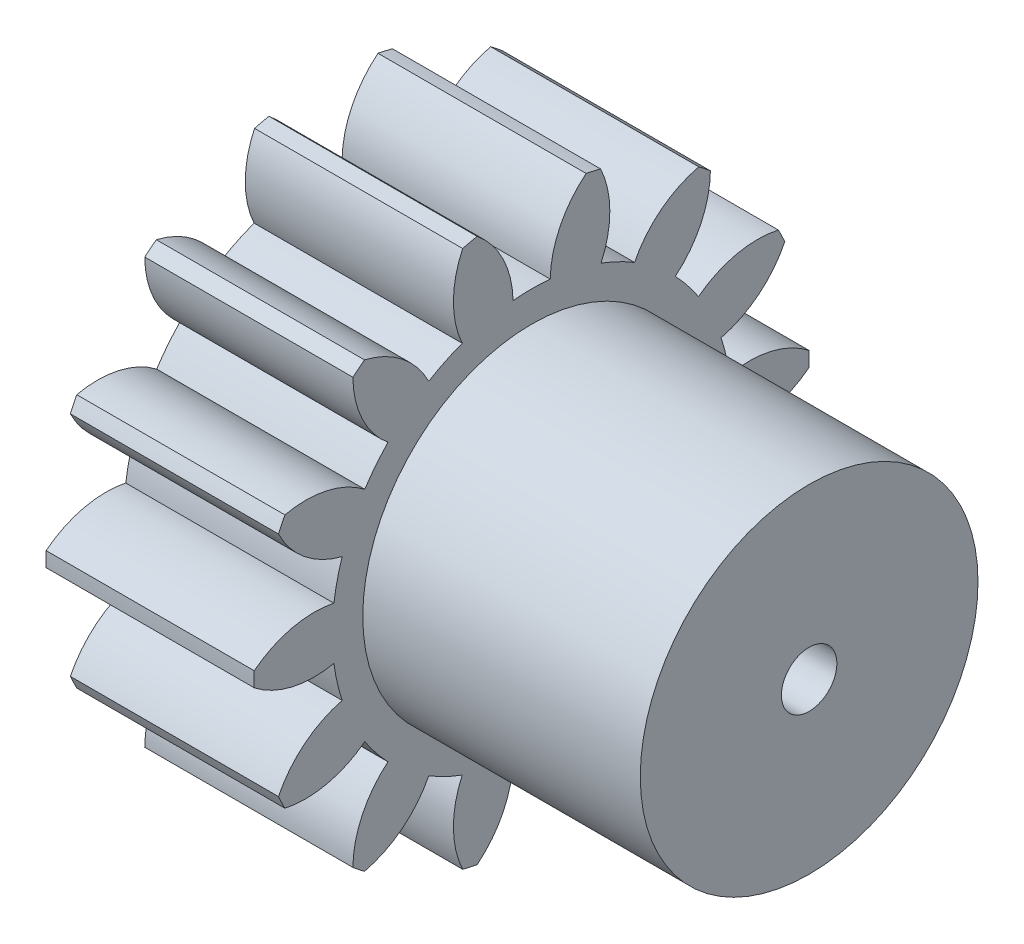
SolidWorks part; units mm, degrees
ref_plane "Plane1" through (0, 0, 0) normal (0, 0, 1) x (1, 0, 0)
ref_plane "Plane2" through (0, 0, 0) normal (0, 1, 0) x (1, 0, 0)
ref_plane "Plane3" through (0, 0, 0) normal (1, 0, 0) x (0, 0, -1)
sketch "HoldingSke" plane through (0, 0, 0) normal (0, 1, 0) x (1, 0, 0)
  line L0 (0, 0) -> (0.3881, -0.0968)
  line L1 (-15, 0) -> (100, 0) construction
  line L2 (0, 0) -> (-2.1039, 2.3779)
  line L3 (0, 0) -> (-11.863, 4.5341)
  line L4 (0, 0) -> (8.3795, 2.0892)
  line L5 (0, 0) -> (-46.8476, -17.4728)
  line L6 (0, 0) -> (-12.4344, -8.3896)
  line L7 (-2.1039, 2.3779) -> (8.6586, 51.2059)
  line L8 (-76.2, 54.61) -> (-75.5, 54.61)
  line L9 (-71.009, 38.7566) -> (-53.1078, 45.2721)
  line L10 (-76.2, 71.12) -> (104.1128, 71.12)
  line L11 (0, 0) -> (-15, 0)
  line L12 (-76.2, 101.6) -> (-76.113, 101.6)
  line L13 (24.9733, 27.94) -> (52.9518, 28.4284)
  line L14 (24.9733, 27.94) -> (24.9743, 27.94)
  line L15 (24.9733, 27.94) -> (100.4006, 29.5858)
  line L16 (-63.627, -2.5) -> (-12.827, -2.5)
  circle A0 centre (0, 0) radius 2
  circle A1 centre (0, 0) radius 14.374
  circle A2 centre (0, 0) radius 37.5
  circle A3 centre (0, 0) radius 2
  dimension "MHD" = 28.748
  dimension "Hub_dia" = 75
  dimension "Bore" = 4
  dimension "MBD" = 4
  dimension "Num_teeth" = 14
  dimension "Pitch" = 0.4
  dimension "Overall_len" = 50
  dimension "Show_teeth" = 14
  dimension "Thickness" = 15
  dimension "OAL" = 50.0001
  dimension "T_dim" = 0.7
  dimension "Ap" = 20
  dimension "H" = 19.05
  dimension "Pitch_radius" = 180.3128
  dimension "Width" = 15
  dimension "Backlash" = 0.087
  dimension "Addendum_fac" = 1
  dimension "Dedendum_fac" = 1.25
  dimension "Clearance_fac" = 0.25
  dimension "Dedendum_add" = 0.001
  dimension "Module" = 2.5
sketch "BasProSke" plane through (0, 0, 0) normal (0, 1, 0) x (1, 0, 0)
  line L0 (-10, 0) -> (60, 0) construction
  line L1 (0, 0) -> (0, 20)
  line L2 (0, 0) -> (15, 0)
  line L3 (15, 0) -> (15, 20)
  line L4 (15, 20) -> (0, 20)
  dimension "Thickness" = 15
  dimension "Diameter" = 40
revolve "Base-Revolve" add sketch "BasProSke" angle 360 about L0
sketch "TooCutSke" plane through (0, 0, 0) normal (1, 0, 0) x (0, 0, -1)
  line L1 (0, 0) -> (0, 107) construction
  line L2 (0, 0) -> (-2.1115, 17.3722) construction
  line L3 (0, 0) -> (-7.7466, 33.9401) construction
  line L4 (-2.1115, 17.3722) -> (-3.8733, 16.97) construction
  arc A0 (1.3395, 14.3115) -> (-1.3395, 14.3115) centre (0, 0) ccw
  arc A1 (3.9542, 19.6311) -> (-3.9542, 19.6311) centre (0, 0) ccw
  circle A2 centre (0, 0) radius 17.5 construction
  circle A3 centre (0, 0) radius 16.4446 construction
  arc A4 (-1.3395, 14.3115) -> (-3.9542, 19.6311) centre (-8.3382, 14.1739) ccw
  arc A5 (3.9542, 19.6311) -> (1.3395, 14.3115) centre (8.3382, 14.1739) ccw
  dimension "Root_dia" = 28.748
  dimension "Overcut_dia" = 40.0508
  dimension "Pitch_dia" = 35
  dimension "Base_dia" = 32.8892
  dimension "Flank_rad" = 7
  dimension "Half_ang" = 12.857
  dimension "Half_CT" = 1.8071
extrude "ToothCut" cut sketch "TooCutSke" along normal through all
fillet "Breaks" [suppressed] radius 0.05
fillet "RootFillets" [suppressed] radius 0.626
pattern_circular "TeethCuts" count 14 every 25.714 about axis through (-10, 0, 0) along (1, 0, 0) of "ToothCut", "RootFillets", "Breaks"
sketch "HubNeaOneSke" plane through (0, 0, 0) normal (-1, 0, 0) x (0, 0, 1)
  circle A0 centre (0, 0) radius 14.374
  dimension "Diameter" = 28.748
extrude "HubNearOne" [suppressed] add sketch "HubNeaOneSke" along normal blind 35.0001
sketch "HubNeaBotSke" plane through (0, 0, 0) normal (-1, 0, 0) x (0, 0, 1)
  circle A0 centre (0, 0) radius 14.374
  dimension "Diameter" = 28.748
extrude "HubNearBoth" [suppressed] add sketch "HubNeaBotSke" along normal blind 17.5
ref_plane "FarPln" through (15, 0, 0) normal (1, 0, 0) x (0, 0, -1)
sketch "HubFarSke" plane through (15, 0, 0) normal (1, 0, 0) x (0, 0, -1)
  circle A0 centre (0, 0) radius 14.374
  dimension "Diameter" = 28.748
extrude "HubFar" [suppressed] add sketch "HubFarSke" along normal blind 17.5
sketch "BorSke" plane through (0, 0, 0) normal (1, 0, 0) x (0, 0, -1)
  circle A0 centre (0, 0) radius 2
  dimension "Diameter" = 4
extrude "Bore" cut sketch "BorSke" along normal mid plane 100.0001
sketch "KeySke" plane through (0, 0, 0) normal (1, 0, 0) x (0, 0, -1)
  line L0 (-0.8, 0) -> (-0.8, 2.7)
  line L1 (-0.8, 2.7) -> (0.8, 2.7)
  line L2 (0.8, 2.7) -> (0.8, 0)
  line L3 (0, 0) -> (0, 34) construction
  line L4 (-0.8, 0) -> (0.8, 0)
  dimension "Offset" = 2.7
  dimension "Width" = 1.6
extrude "Keyway" [suppressed] cut sketch "KeySke" along normal mid plane 100.0001
pattern_circular "Keyway2" [suppressed] count 2 every 90 about axis through (-10, 0, 0) along (1, 0, 0)
sketch "Sketch1" plane through (15, 0, 0) normal (1, 0, 0) x (0, 0, -1)
  circle A0 centre (0, 0) radius 12.1701
extrude "Boss-Extrude1" add sketch "Sketch1" along normal blind 20 contours A0
sketch "Sketch3" plane through (35, 0, 0) normal (1, 0, 0) x (0, 0, -1)
  circle A0 centre (0, 0) radius 2 construction
  circle A1 centre (0, 0) radius 2
extrude "Cut-Extrude1" cut sketch "Sketch3" against normal through all
equation "' \"Module@HoldingSke\" = 6.35"
equation "' \"Num_teeth@HoldingSke\" = 12"
equation "' \"Ap@HoldingSke\" =  20"
equation "' \"Ap@HoldingSke\" = 20"
equation "' \"Width@HoldingSke\" = 0.5 * 25.4"
equation "' \"Hub_dia@HoldingSke\"= 1 * 25.4"
equation "' \"Hub_dia@HoldingSke\" = 1 * 25.4"
equation "' \"Overall_len@HoldingSke\" = 1.0 * 25.4"
equation "' \"Bore@HoldingSke\" = 0.75 * 25.4"
equation "' \"T_dim@HoldingSke\" = 0.1 * 25.4"
equation "' \"Width@KeySke\" = 0.25 * 25.4"
equation "' \"Show_teeth@HoldingSke\" = 13"
equation "' \"Backlash@HoldingSke\" = 0.009 * 25.4"
equation "' \"Addendum_fac@HoldingSke\" = 1.0"
equation "' \"Dedendum_fac@HoldingSke\" = 1.25"
equation "' \"Dedendum_add@HoldingSke\" = 0.00005 * 25.4"
equation "' \"Clearance_fac@HoldingSke\" = 0.25"
equation "\"Pitch@HoldingSke\" = 1 / \"Module@HoldingSke\""
equation "\"Overcut_dia@TooCutSke\" = (\"Num_teeth@HoldingSke\" + 2 * \"Addendum_fac@HoldingSke\") / \"Pitch@HoldingSke\" + 0.002 * 25.4"
equation "\"Pitch_dia@TooCutSke\" = \"Num_teeth@HoldingSke\" / \"Pitch@HoldingSke\""
equation "\"Base_dia@TooCutSke\" = \"Num_teeth@HoldingSke\" / \"Pitch@HoldingSke\" * cos((\"Ap@HoldingSke\"  * 3.14159265 / 180))"
equation "\"Root_dia@TooCutSke\" = (\"Num_teeth@HoldingSke\" + 2) / \"Pitch@HoldingSke\" - 2 * (\"Addendum_fac@HoldingSke\" + \"Dedendum_fac@HoldingSke\") / \"Pitch@HoldingSke\" - \"Dedendum_add@HoldingSke\" * 2"
equation "\"Half_ang@TooCutSke\" = 180 / \"Num_teeth@HoldingSke\""
equation "\"Half_CT@TooCutSke\" = \"Num_teeth@HoldingSke\" / \"Pitch@HoldingSke\" * sin((3.14159265 / 2 / \"Num_teeth@HoldingSke\")) / 2 - 7 * \"Backlash@HoldingSke\" / 4"
equation "\"Flank_rad@TooCutSke\" = \"Num_teeth@HoldingSke\" / \"Pitch@HoldingSke\" / 5"
equation "\"Radius@RootFillets\" = \"Clearance_fac@HoldingSke\" / \"Pitch@HoldingSke\" + \"Dedendum_add@HoldingSke\""
equation "\"Break_rad@Breaks\" = 0.02 / \"Pitch@HoldingSke\""
equation "\"Thickness@HoldingSke\" = \"Width@HoldingSke\""
equation "\"OAL@HoldingSke\" = \"Thickness@HoldingSke\""
equation "\"MHD@HoldingSke\" = (\"Num_teeth@HoldingSke\" + 2) / \"Pitch@HoldingSke\" - 2 * (\"Addendum_fac@HoldingSke\" + \"Dedendum_fac@HoldingSke\")  / \"Pitch@HoldingSke\" - \"Dedendum_add@HoldingSke\" * 2"
equation "\"MBD@HoldingSke\" = (\"Num_teeth@HoldingSke\" + 2) / \"Pitch@HoldingSke\" - 2 * (\"Addendum_fac@HoldingSke\" + \"Dedendum_fac@HoldingSke\")  / \"Pitch@HoldingSke\" - \"Dedendum_add@HoldingSke\" * 2 - 0.002 * 25.4"
equation "\"MHD@HoldingSke\" = ((sgn( \"MHD@HoldingSke\" - \"Hub_dia@HoldingSke\" )-1)*( \"MHD@HoldingSke\" - \"Hub_dia@HoldingSke\" ))/-2+ \"Hub_dia@HoldingSke\""
equation "\"MBD@HoldingSke\" = ((sgn( \"MBD@HoldingSke\" - \"Bore@HoldingSke\" )-1)*( \"MBD@HoldingSke\" - \"Bore@HoldingSke\" ))/-2+ \"Bore@HoldingSke\""
equation "\"OAL@HoldingSke\" = ((sgn( \"OAL@HoldingSke\" - \"Overall_len@HoldingSke\" )+1)*( \"OAL@HoldingSke\" - \"Overall_len@HoldingSke\" ))/2 + \"Overall_len@HoldingSke\" + 0.000002 * 25.4"
equation "\"Num_teeth@TeethCuts\" = int( \"Show_teeth@HoldingSke\" ) + 1"
equation "\"Num_teeth@TeethCuts\" = ((sgn( \"Num_teeth@TeethCuts\" - \"Num_teeth@HoldingSke\" )-1)*( \"Num_teeth@TeethCuts\" - \"Num_teeth@HoldingSke\" ))/-2+ \"Num_teeth@HoldingSke\""
equation "\"Num_teeth@TeethCuts\" = ((sgn( \"Num_teeth@TeethCuts\" - 2.0)+1)*( \"Num_teeth@TeethCuts\" - 2.0))/2 +2.0"
equation "\"Angle@TeethCuts\" = 360.0 / \"Num_teeth@HoldingSke\""
equation "\"Diameter@BasProSke\" = (\"Num_teeth@HoldingSke\" + 2 * \"Addendum_fac@HoldingSke\") / \"Pitch@HoldingSke\""
equation "\"Thickness@BasProSke\"  = \"Thickness@HoldingSke\""
equation "' \"Fillet_rad@BasProSke\" =  \"Thickness@HoldingSke\" * 0.05"
equation "' \"Fillet_rad@BasProSke\" = \"Thickness@HoldingSke\" * 0.05"
equation "\"MHD@HoldingSke\" = ((sgn( \"MHD@HoldingSke\" - \"Root_dia@TooCutSke\" )-1)*( \"MHD@HoldingSke\" - \"Root_dia@TooCutSke\" ))/-2+ \"Root_dia@TooCutSke\""
equation "\"Diameter@HubNeaOneSke\" = \"MHD@HoldingSke\""
equation "\"Length@HubNearOne\" = \"OAL@HoldingSke\" - \"Thickness@BasProSke\""
equation "\"Diameter@HubNeaBotSke\" = \"MHD@HoldingSke\""
equation "\"Length@HubNearBoth\" = ( \"OAL@HoldingSke\" - \"Thickness@BasProSke\" ) / 2.0"
equation "\"Thickness@FarPln\" = \"Thickness@BasProSke\""
equation "\"Diameter@HubFarSke\" = \"MHD@HoldingSke\""
equation "\"Length@HubFar\" = ( \"OAL@HoldingSke\" - \"Thickness@BasProSke\" ) / 2.0"
equation "\"Diameter@BorSke\" = \"MBD@HoldingSke\""
equation "\"D1@Bore\" = \"OAL@HoldingSke\" * 2.0"
equation "\"D1@Keyway\" = \"OAL@HoldingSke\" * 2.0"
equation "\"Offset@KeySke\" = \"T_dim@HoldingSke\" + \"MBD@HoldingSke\" / 2.0"
